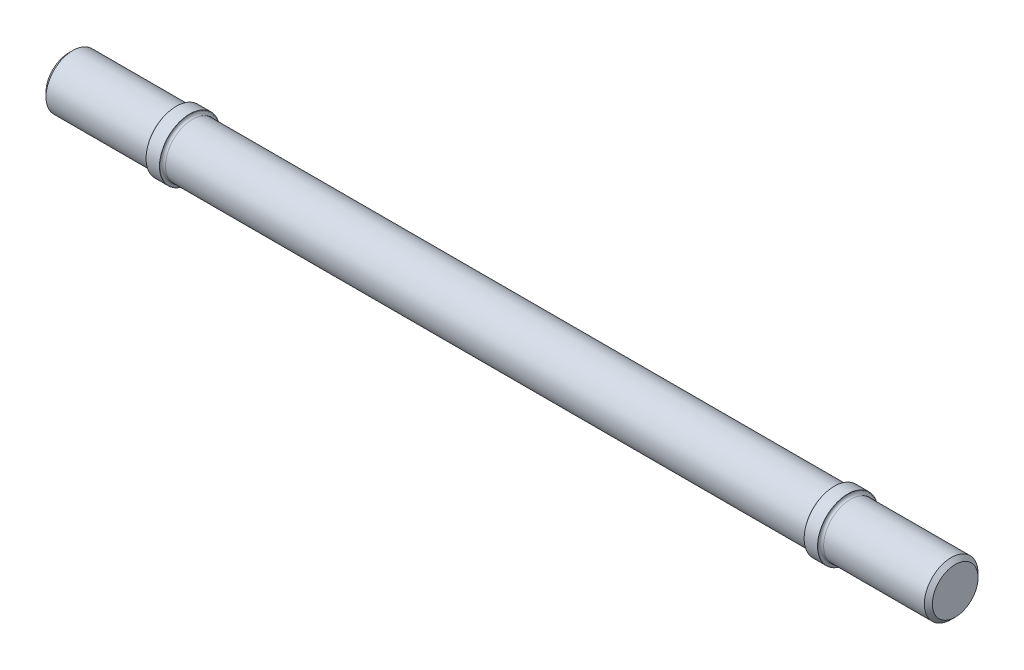
SolidWorks part; units mm, degrees
ref_plane "Front Plane" through (0, 0, 0) normal (0, 0, 1) x (1, 0, 0)
ref_plane "Top Plane" through (0, 0, 0) normal (0, 1, 0) x (1, 0, 0)
ref_plane "Right Plane" through (0, 0, 0) normal (1, 0, 0) x (0, 0, -1)
sketch "Sketch2" plane through (0, 0, 0) normal (0, 0, 1) x (1, 0, 0)
  line L0 (0, 0) -> (75.2934, 0) construction
  line L1 (8, 2) -> (8, 2.25)
  line L2 (0, 0) -> (66, 0)
  line L3 (0, 0) -> (0, 2)
  line L4 (0, 2) -> (8, 2)
  line L5 (66, 0) -> (66, 2)
  line L6 (8, 2.25) -> (9, 2.25)
  line L7 (9, 2.25) -> (9, 2)
  line L8 (9, 2) -> (57, 2)
  line L9 (57, 2) -> (57, 2.25)
  line L10 (57, 2.25) -> (58, 2.25)
  line L11 (58, 2.25) -> (58, 2)
  line L12 (58, 2) -> (66, 2)
  line L13 (8, 2) -> (8, 0)
  line L14 (10, 2) -> (10, 0)
  line L15 (18, 2) -> (18, 0)
  line L16 (42, 2) -> (42, 0)
  line L17 (50, 2) -> (50, 0)
  line L18 (58, 2) -> (58, 0)
  point P29 (18, 1)
  dimension "D1" = 66
  dimension "D2" = 4
  dimension "D3" = 8
  dimension "D4" = 1
  dimension "D5" = 0.25
  dimension "D6" = 57
  dimension "D7" = 1
  dimension "D8" = 0.25
  dimension "D9" = 10
  dimension "D10" = 18
  dimension "D11" = 42
  dimension "D12" = 50
  dimension "D13" = 58
revolve "Revolve1" add sketch "Sketch2" angle 360 about L0
ref_plane "Plane1" through (8, 0, 0) normal (-1, 0, 0) x (0, 0, 1)
ref_plane "Plane2" through (18, 0, 0) normal (-1, 0, 0) x (0, 0, 1)
ref_plane "Plane3" through (42, 0, 0) normal (-1, 0, 0) x (0, 0, 1)
ref_plane "Plane4" through (52, 0, 0) normal (-1, 0, 0) x (0, 0, 1)
sketch "Sketch3" plane through (0, 0, 0) normal (0, 0, 1) x (1, 0, 0)
  line L0 (0, 0) -> (0, 6.8254) construction
  line L1 (0, 2) -> (0, -2) construction
  line L2 (8, 6.2547) -> (8, -4.5324) construction
  line L3 (8, 1.87) -> (8, -1.87) construction
  line L4 (18, 4.7707) -> (18, -4.0758) construction
  line L5 (18, 1.87) -> (18, -1.87) construction
  line L6 (42, 6.2547) -> (42, -4.5324) construction
  line L7 (42, 1.87) -> (42, -1.87) construction
  line L8 (52, 5.8053) -> (52, -4.5324) construction
  line L9 (52, 1.87) -> (52, -1.87) construction
fillet "Fillet1" radius 0.2 4 edges at (8, 0, 2) (9, 0, 2) (57, 0, 2) (58, 0, 2)
chamfer "Chamfer1" distance 0.3 angle 45 2 edges at (66, 0, 2) (0, 0, 2)
